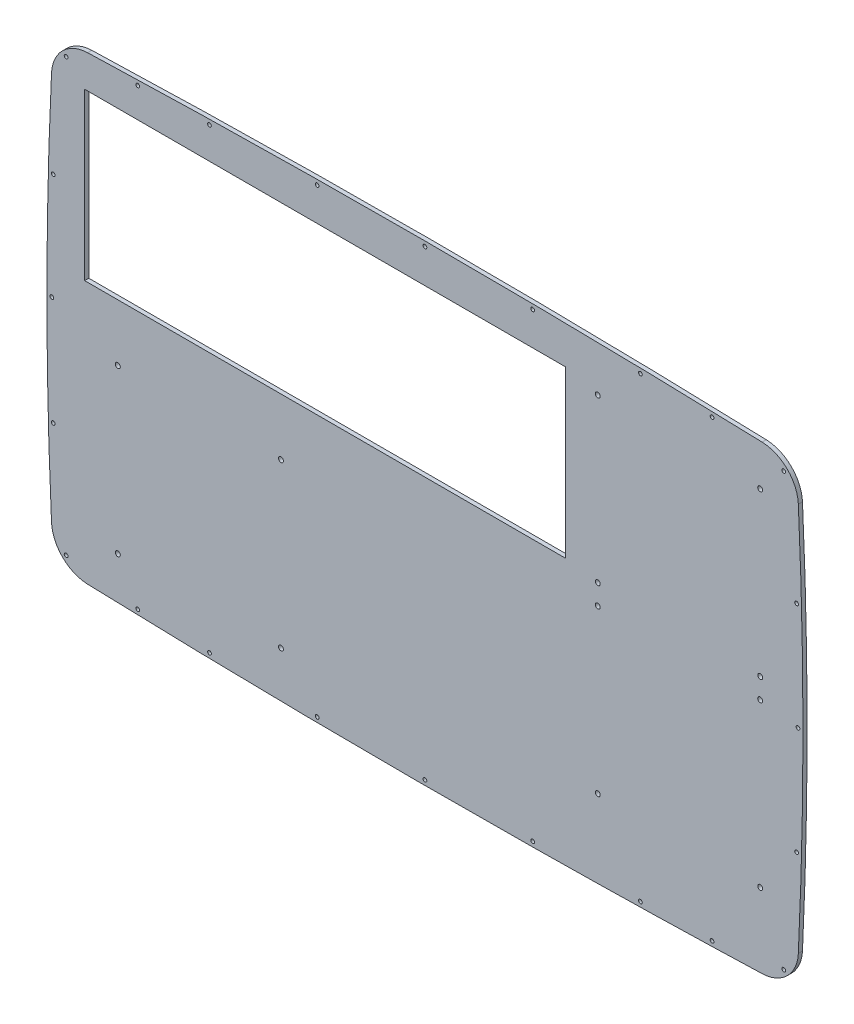
SolidWorks part; units mm, degrees
ref_plane "Front" through (0, 0, 0) normal (0, 0, 1) x (1, 0, 0)
ref_plane "Top" through (0, 0, 0) normal (0, 1, 0) x (1, 0, 0)
ref_plane "Right" through (0, 0, 0) normal (1, 0, 0) x (0, 0, -1)
sketch "Sketch1" plane through (0, 0, 0) normal (0, 0, 1) x (1, 0, 0)
  line L0 (79.622, -180.7786) -> (85.5592, -180.7149)
  line L1 (223.1034, -177.9577) -> (258.4236, -176.8528)
  circle A0 centre (-274.9542, -165.9116) radius 1.435
  arc A93 (-279.7814, -166.2105) -> (-275.1845, -170.7425) centre (-257.4604, -148.1676) ccw
  arc A94 (275.1845, -170.7425) -> (279.7814, -166.2105) centre (257.4604, -148.1676) ccw
  circle A100 centre (-274.9542, 164.9337) radius 1.4351
  circle A101 centre (-284.8103, 82.061) radius 1.4351
  circle A102 centre (-285.9024, 0) radius 1.4351
  circle A103 centre (-284.8103, -83.0389) radius 1.4351
  arc A104 (-258.4236, -176.8528) -> (-223.1034, -177.9577) centre (0, 7519.4009) ccw
  circle A105 centre (-220.0271, -174.2607) radius 1.4351
  circle A106 centre (-165.1, -175.6347) radius 1.4351
  arc A107 (-162.2131, -179.4816) -> (-85.5592, -180.7149) centre (0, 7519.4009) ccw
  arc A108 (-168.1492, -179.3542) -> (-162.2131, -179.4816) centre (0, 7519.4009) ccw
  circle A109 centre (-82.55, -176.963) radius 1.4351
  circle A110 centre (0, -177.4057) radius 1.4351
  circle A111 centre (82.55, -176.963) radius 1.4351
  circle A112 centre (165.1, -175.6347) radius 1.4351
  circle A113 centre (220.0271, -174.2607) radius 1.4351
  circle A114 centre (284.8103, -83.0389) radius 1.4351
  circle A115 centre (285.9024, 0) radius 1.4351
  circle A116 centre (284.8103, 82.061) radius 1.4351
  circle A117 centre (274.9542, 164.9337) radius 1.4351
  circle A118 centre (220.0271, 173.2828) radius 1.4351
  circle A119 centre (165.1, 174.6568) radius 1.4351
  circle A120 centre (82.55, 175.9851) radius 1.4351
  circle A121 centre (0, 176.4278) radius 1.4351
  circle A122 centre (-82.55, 175.9851) radius 1.4351
  circle A123 centre (-220.0271, 173.2828) radius 1.4351
  circle A124 centre (-165.1, 174.6568) radius 1.4351
  arc A125 (-162.2131, 178.5037) -> (-168.1492, 178.3763) centre (0, -7520.3788) ccw
  arc A126 (-85.5592, 179.737) -> (-162.2131, 178.5037) centre (0, -7520.3788) ccw
  arc A127 (-79.622, 179.8007) -> (-85.5592, 179.737) centre (0, -7520.3788) ccw
  arc A128 (-2.9688, 180.2118) -> (-79.622, 179.8007) centre (0, -7520.3788) ccw
  arc A129 (2.9688, 180.2118) -> (-2.9688, 180.2118) centre (0, -7520.3788) ccw
  arc A130 (79.622, 179.8007) -> (2.9688, 180.2118) centre (0, -7520.3788) ccw
  arc A131 (85.5592, 179.737) -> (79.622, 179.8007) centre (0, -7520.3788) ccw
  arc A132 (162.2131, 178.5037) -> (85.5592, 179.737) centre (0, -7520.3788) ccw
  arc A133 (168.1492, 178.3763) -> (162.2131, 178.5037) centre (0, -7520.3788) ccw
  arc A134 (217.1671, 177.1496) -> (168.1492, 178.3763) centre (0, -7520.3788) ccw
  arc A135 (223.1034, 176.9798) -> (217.1671, 177.1496) centre (0, -7520.3788) ccw
  arc A136 (258.4236, 175.8749) -> (223.1034, 176.9798) centre (0, -7520.3788) ccw
  arc A137 (275.1845, 169.7646) -> (258.4236, 175.8749) centre (257.4604, 147.1897) ccw
  arc A138 (279.7814, 165.2326) -> (275.1845, 169.7646) centre (257.4604, 147.1897) ccw
  arc A139 (286.1291, 148.559) -> (279.7814, 165.2326) centre (257.4604, 147.1897) ccw
  arc A140 (288.513, 85.1308) -> (286.1291, 148.559) centre (-2834.64, -0.4889) ccw
  arc A141 (288.6701, 79.1915) -> (288.513, 85.1308) centre (-2834.64, -0.4889) ccw
  arc A142 (289.6845, 2.9713) -> (288.6701, 79.1915) centre (-2834.64, -0.4889) ccw
  arc A143 (289.6854, -2.9701) -> (289.6845, 2.9713) centre (-2834.64, -0.4889) ccw
  arc A144 (288.6701, -80.1694) -> (289.6854, -2.9701) centre (-2834.64, -0.4889) ccw
  arc A145 (288.513, -86.1087) -> (288.6701, -80.1694) centre (-2834.64, -0.4889) ccw
  arc A146 (286.1291, -149.5369) -> (288.513, -86.1087) centre (-2834.64, -0.4889) ccw
  arc A147 (279.7814, -166.2105) -> (286.1291, -149.5369) centre (257.4604, -148.1676) ccw
  arc A148 (275.1845, -170.7425) -> (279.7814, -166.2105) centre (257.4604, -148.1676) ccw
  arc A149 (258.4236, -176.8528) -> (275.1845, -170.7425) centre (257.4604, -148.1676) ccw
  arc A150 (217.1671, -178.1275) -> (223.1034, -177.9577) centre (0, 7519.4009) ccw
  arc A151 (168.1492, -179.3542) -> (217.1671, -178.1275) centre (0, 7519.4009) ccw
  arc A152 (85.5592, -180.7149) -> (162.2131, -179.4816) centre (0, 7519.4009) ccw
  arc A153 (162.2131, -179.4816) -> (168.1492, -179.3542) centre (0, 7519.4009) ccw
  arc A154 (2.9688, -181.1897) -> (79.622, -180.7786) centre (0, 7519.4009) ccw
  arc A155 (-2.9688, -181.1897) -> (2.9688, -181.1897) centre (0, 7519.4009) ccw
  arc A156 (-79.622, -180.7786) -> (-2.9688, -181.1897) centre (0, 7519.4009) ccw
  arc A157 (-85.5592, -180.7149) -> (-79.622, -180.7786) centre (0, 7519.4009) ccw
  arc A158 (-217.1671, -178.1275) -> (-168.1492, -179.3542) centre (0, 7519.4009) ccw
  arc A159 (-223.1034, -177.9577) -> (-217.1671, -178.1275) centre (0, 7519.4009) ccw
  arc A160 (-275.1845, -170.7425) -> (-258.4236, -176.8528) centre (-257.4604, -148.1676) ccw
  arc A161 (-279.7814, -166.2105) -> (-275.1845, -170.7425) centre (-257.4604, -148.1676) ccw
  arc A162 (-286.1291, -149.5369) -> (-279.7814, -166.2105) centre (-257.4604, -148.1676) ccw
  arc A163 (-288.513, -86.1087) -> (-286.1291, -149.5369) centre (2834.64, -0.4889) ccw
  arc A164 (-288.6701, -80.1694) -> (-288.513, -86.1087) centre (2834.64, -0.4889) ccw
  arc A165 (-289.6854, -2.9701) -> (-288.6701, -80.1694) centre (2834.64, -0.4889) ccw
  arc A166 (-289.6845, 2.9713) -> (-289.6854, -2.9701) centre (2834.64, -0.4889) ccw
  arc A167 (-288.6701, 79.1915) -> (-289.6845, 2.9713) centre (2834.64, -0.4889) ccw
  arc A168 (-288.513, 85.1308) -> (-288.6701, 79.1915) centre (2834.64, -0.4889) ccw
  arc A169 (-286.1291, 148.559) -> (-288.513, 85.1308) centre (2834.64, -0.4889) ccw
  arc A170 (-279.7814, 165.2326) -> (-286.1291, 148.559) centre (-257.4604, 147.1897) ccw
  arc A171 (-275.1845, 169.7646) -> (-279.7814, 165.2326) centre (-257.4604, 147.1897) ccw
  arc A172 (-258.4236, 175.8749) -> (-275.1845, 169.7646) centre (-257.4604, 147.1897) ccw
  arc A173 (-223.1034, 176.9798) -> (-258.4236, 175.8749) centre (0, -7520.3788) ccw
  arc A174 (-217.1671, 177.1496) -> (-223.1034, 176.9798) centre (0, -7520.3788) ccw
  arc A175 (-168.1492, 178.3763) -> (-217.1671, 177.1496) centre (0, -7520.3788) ccw
  circle A176 centre (274.9542, -165.9116) radius 1.4351
extrude "Boss-Extrude1" add sketch "Sketch1" along normal blind 3.175
sketch "Sketch2" plane through (0, 0, 3.175) normal (0, 0, 1) x (1, 0, 0)
  line L0 (-260.7291, 150.4749) -> (-260.7291, 23.4749)
  line L1 (107.5709, 23.4749) -> (-260.7291, 23.4749)
  line L2 (107.5709, 23.4749) -> (107.5709, 150.4749)
  line L3 (107.5709, 150.4749) -> (-260.7291, 150.4749)
  arc A0 (258.4236, 175.8749) -> (-258.4236, 175.8749) centre (0, -7520.3788) ccw construction
  arc A1 (258.4236, 175.8749) -> (-258.4236, 175.8749) centre (0, -7520.3788) ccw
  dimension "D2" = 25.4
  dimension "D1" = 25.4
  dimension "D3" = 127
  dimension "D4" = 368.3
extrude "Cut-Extrude1" cut sketch "Sketch2" against normal through all contours L2 L3 L0 L1
sketch "Sketch4" plane through (0, 0, 0) normal (0, 0, -1) x (-1, 0, 0)
  circle A0 centre (-256.9191, 144.1249) radius 1.8987
  circle A1 centre (-132.4191, 144.1249) radius 1.8987
  circle A2 centre (-256.9191, 19.6249) radius 1.8987
  circle A3 centre (-256.9191, 4.1249) radius 1.8987
  circle A4 centre (-132.4191, 19.6249) radius 1.8987
  circle A5 centre (-132.4191, 4.1249) radius 1.8987
  circle A6 centre (-256.9191, -120.3751) radius 1.8987
  circle A7 centre (-132.4191, -120.3751) radius 1.8987
  dimension "D7" = 3.7973
  dimension "D1" = 124.5
  dimension "D2" = 124.5
  dimension "D3" = 140
  dimension "D4" = 264.5
  dimension "D5" = 29.21
  dimension "D6" = 31.75
extrude "Cut-Extrude2" cut sketch "Sketch4" against normal through all
sketch "Sketch5" plane through (0, 0, 0) normal (0, 0, -1) x (-1, 0, 0)
  circle A0 centre (235.3291, -145.1028) radius 1.8987
  circle A1 centre (110.3291, -145.1028) radius 1.8987
  circle A2 centre (110.3291, -20.1028) radius 1.8987
  circle A3 centre (235.3291, -20.1028) radius 1.8987
  dimension "D1" = 3.7973
  dimension "D4" = 50.8
  dimension "D2" = 125
  dimension "D3" = 125
  dimension "D5" = 31.75
extrude "Cut-Extrude3" cut sketch "Sketch5" against normal through all
